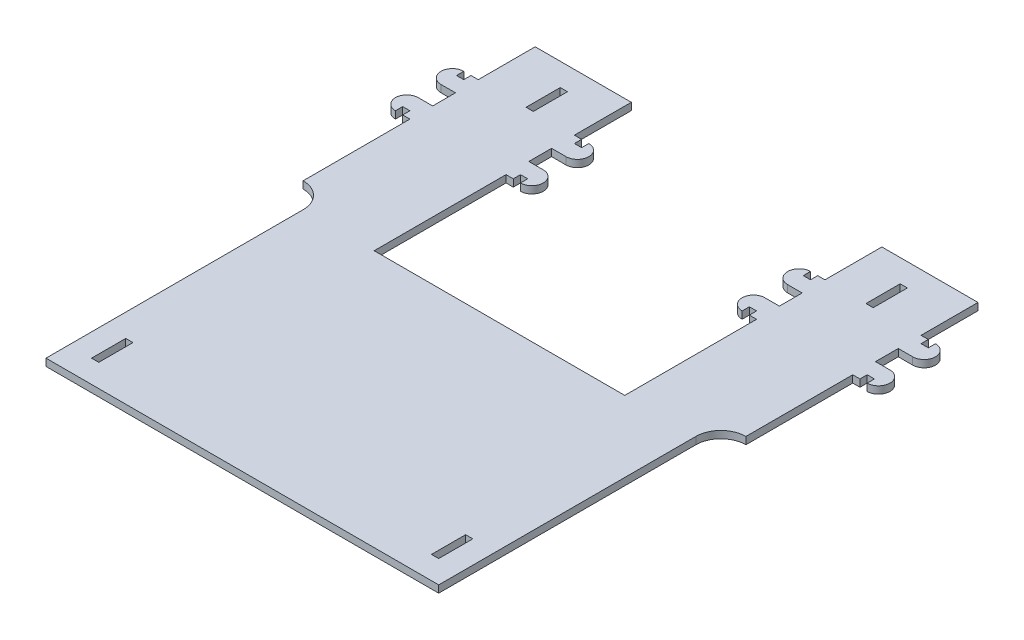
SolidWorks part; units mm, degrees
ref_plane "Front Plane" through (0, 0, 0) normal (0, 0, 1) x (1, 0, 0)
ref_plane "Top Plane" through (0, 0, 0) normal (0, 1, 0) x (1, 0, 0)
ref_plane "Right Plane" through (0, 0, 0) normal (1, 0, 0) x (0, 0, -1)
sketch "Sketch1" plane through (0, 0, 0) normal (0, 1, 0) x (1, 0, 0)
  line L0 (76.2, 102.88) -> (76.2, 87.88)
  line L1 (-76.2, 102.88) -> (-73.025, 102.88)
  line L2 (-76.2, 102.88) -> (-76.2, 87.88)
  line L3 (-76.2, -102.88) -> (-73.025, -102.88)
  line L4 (76.2, 102.88) -> (76.2, 87.88)
  line L5 (-55, 0) -> (55, 0)
  line L6 (-55, 0) -> (55, 0)
  line L7 (76.2, 87.88) -> (73.025, 87.88)
  line L8 (73.025, 87.88) -> (73.025, 102.88)
  line L9 (73.025, 102.88) -> (76.2, 102.88)
  line L10 (97.2, 11) -> (97.2, 57.88)
  line L11 (97.2, 112.88) -> (86.2, 112.88)
  line L12 (-73.025, 102.88) -> (-76.2, 102.88)
  line L13 (-73.025, 87.88) -> (-73.025, 102.88)
  line L14 (-76.2, 87.88) -> (-73.025, 87.88)
  line L15 (-76.2, 102.88) -> (-76.2, 87.88)
  line L16 (73.025, -102.88) -> (76.2, -102.88)
  line L17 (73.025, -87.88) -> (73.025, -102.88)
  line L18 (76.2, -87.88) -> (73.025, -87.88)
  line L19 (76.2, -102.88) -> (76.2, -87.88)
  line L20 (-73.025, -102.88) -> (-76.2, -102.88)
  line L21 (-73.025, -87.88) -> (-73.025, -102.88)
  line L22 (-76.2, -87.88) -> (-73.025, -87.88)
  line L23 (-76.2, -102.88) -> (-76.2, -87.88)
  line L24 (73.025, -102.88) -> (76.2, -102.88)
  line L25 (-73.025, -102.88) -> (-76.2, -102.88)
  line L26 (76.2, -112.88) -> (-76.2, -112.88)
  line L27 (-55, 0) -> (-55, 57.88)
  line L28 (86.2, -102.88) -> (86.2, 0)
  line L29 (76.2, -87.88) -> (76.2, -102.88)
  line L30 (76.2, 102.88) -> (76.2, 87.88)
  line L31 (76.2, -102.88) -> (73.025, -102.88)
  line L32 (76.2, -87.88) -> (76.2, -102.88)
  line L33 (76.2, 112.88) -> (55, 112.88)
  line L34 (73.025, 102.88) -> (76.2, 102.88)
  line L35 (-97.2, 112.88) -> (-86.2, 112.88)
  line L36 (-86.2, -102.88) -> (-86.2, 0)
  line L37 (-76.2, -87.88) -> (-76.2, -102.88)
  line L39 (86.2, 112.88) -> (76.2, 112.88)
  line L40 (-76.2, 112.88) -> (-86.2, 112.88)
  line L42 (-86.2, -102.88) -> (-86.2, -112.88)
  line L43 (-86.2, -112.88) -> (-76.2, -112.88)
  line L44 (76.2, -112.88) -> (86.2, -112.88)
  line L45 (86.2, -112.88) -> (86.2, -102.88)
  line L46 (-97.2, 11) -> (-97.2, 57.88)
  line L47 (55, 0) -> (55, 57.88)
  line L48 (-97.2, 87.88) -> (-97.2, 112.88)
  line L49 (-97.2, 67.88) -> (-97.2, 77.88)
  line L50 (-55, 112.88) -> (-76.2, 112.88)
  line L51 (-55, 67.88) -> (-55, 77.88)
  line L52 (-55, 87.88) -> (-55, 112.88)
  line L54 (97.2, 87.88) -> (100.375, 87.88)
  line L55 (100.375, 87.88) -> (100.375, 84.705)
  line L56 (100.375, 84.705) -> (103.55, 84.705)
  line L57 (103.55, 84.705) -> (103.55, 87.88)
  line L58 (103.55, 87.88) -> (103.55, 84.705)
  line L59 (103.55, 77.88) -> (97.2, 77.88)
  line L60 (55, 87.88) -> (55, 112.88)
  line L61 (97.2, 77.88) -> (97.2, 67.88)
  line L62 (97.2, 67.88) -> (103.55, 67.88)
  line L64 (97.2, 57.88) -> (100.375, 57.88)
  line L65 (100.375, 57.88) -> (100.375, 61.055)
  line L66 (100.375, 61.055) -> (103.55, 61.055)
  line L67 (103.55, 61.055) -> (103.55, 57.88)
  line L68 (103.55, 57.88) -> (103.55, 61.055)
  line L69 (-97.2, 67.88) -> (-103.55, 67.88)
  line L70 (-103.55, 61.055) -> (-103.55, 57.88)
  line L71 (-100.375, 61.055) -> (-103.55, 61.055)
  line L72 (-100.375, 57.88) -> (-100.375, 61.055)
  line L73 (-97.2, 57.88) -> (-100.375, 57.88)
  line L74 (-103.55, 77.88) -> (-97.2, 77.88)
  line L75 (-103.55, 84.705) -> (-103.55, 87.88)
  line L76 (-100.375, 84.705) -> (-103.55, 84.705)
  line L77 (-100.375, 87.88) -> (-100.375, 84.705)
  line L78 (-97.2, 87.88) -> (-100.375, 87.88)
  line L83 (-97.2, 57.88) -> (-100.375, 57.88)
  line L84 (-100.375, 57.88) -> (-100.375, 61.055)
  line L85 (-100.375, 61.055) -> (-103.55, 61.055)
  line L86 (-103.55, 61.055) -> (-103.55, 57.88)
  line L87 (-97.2, 67.88) -> (-103.55, 67.88)
  line L88 (-103.55, 77.88) -> (-97.2, 77.88)
  line L89 (-103.55, 84.705) -> (-103.55, 87.88)
  line L90 (-100.375, 84.705) -> (-103.55, 84.705)
  line L91 (-100.375, 87.88) -> (-100.375, 84.705)
  line L92 (-97.2, 87.88) -> (-100.375, 87.88)
  line L93 (55, 67.88) -> (55, 77.88)
  line L94 (-55, 67.88) -> (-48.65, 67.88)
  line L95 (-48.65, 61.055) -> (-48.65, 57.88)
  line L96 (-51.825, 61.055) -> (-48.65, 61.055)
  line L97 (-51.825, 57.88) -> (-51.825, 61.055)
  line L98 (-55, 57.88) -> (-51.825, 57.88)
  line L100 (-55, 87.88) -> (-51.825, 87.88)
  line L101 (-51.825, 87.88) -> (-51.825, 84.705)
  line L102 (-51.825, 84.705) -> (-48.65, 84.705)
  line L103 (-48.65, 84.705) -> (-48.65, 87.88)
  line L104 (-48.65, 77.88) -> (-55, 77.88)
  line L106 (97.2, 67.88) -> (97.2, 77.88)
  line L107 (97.2, 87.88) -> (97.2, 112.88)
  line L108 (55, 57.88) -> (51.825, 57.88)
  line L109 (51.825, 57.88) -> (51.825, 61.055)
  line L110 (51.825, 61.055) -> (48.65, 61.055)
  line L111 (48.65, 61.055) -> (48.65, 57.88)
  line L112 (55, 67.88) -> (48.65, 67.88)
  line L113 (48.65, 77.88) -> (55, 77.88)
  line L114 (48.65, 84.705) -> (48.65, 87.88)
  line L115 (51.825, 84.705) -> (48.65, 84.705)
  line L116 (51.825, 87.88) -> (51.825, 84.705)
  line L117 (55, 87.88) -> (51.825, 87.88)
  arc A0 (86.2, 0) -> (97.2, 11) centre (97.2, 0) cw
  arc A1 (-86.2, 0) -> (-97.2, 11) centre (-97.2, 0) ccw
  arc A2 (103.55, 87.88) -> (103.55, 77.88) centre (103.55, 82.88) cw
  arc A3 (103.55, 57.88) -> (103.55, 67.88) centre (103.55, 62.88) ccw
  arc A4 (-103.55, 57.88) -> (-103.55, 67.88) centre (-103.55, 62.88) cw
  arc A5 (-103.55, 87.88) -> (-103.55, 77.88) centre (-103.55, 82.88) ccw
  arc A6 (-103.55, 57.88) -> (-103.55, 67.88) centre (-103.55, 62.88) cw
  arc A7 (-103.55, 87.88) -> (-103.55, 77.88) centre (-103.55, 82.88) ccw
  arc A8 (-48.65, 57.88) -> (-48.65, 67.88) centre (-48.65, 62.88) ccw
  arc A9 (-48.65, 87.88) -> (-48.65, 77.88) centre (-48.65, 82.88) cw
  arc A10 (48.65, 57.88) -> (48.65, 67.88) centre (48.65, 62.88) cw
  arc A11 (48.65, 87.88) -> (48.65, 77.88) centre (48.65, 82.88) ccw
  point P0 (0, 0)
  point P35 (0, 0)
extrude "Boss-Extrude1" add sketch "Sketch1" along normal blind 3.175 contours L114 A11 L113 L93 L112 A10 L111 L110 L109 L108 L47 L5 L27 L98 L97 L96 L95 A8 L94 L51 L104 A9 L103 L102 L101 L100 L52 L50 L40 L35 L48 L78 L77 L76 L75 A5 L74 L49 L69 A4 L70 L71 L72 L73 L46 A1 L36 L42 L43 L26 L44
sketch "Sketch2" plane through (0, 0, 0) normal (0, 1, 0) x (1, 0, 0)
  line L0 (-55, 0) -> (-55, -112.88)
  line L1 (-86.2, -112.88) -> (86.2, -112.88) construction
  line L2 (55, 0) -> (55, -112.88)
  line L3 (55, -112.88) -> (-55, -112.88)
  line L4 (-55, 0) -> (55, 0)
